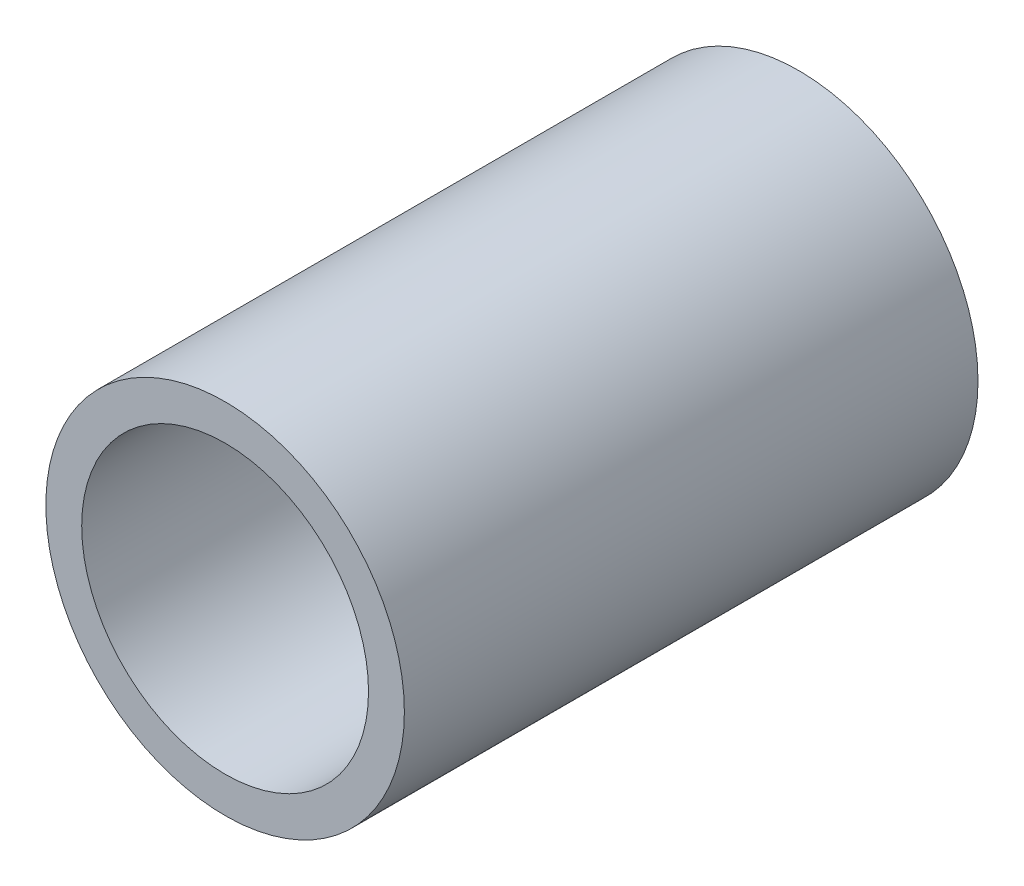
SolidWorks part; units mm, degrees
ref_plane "Front Plane" through (0, 0, 0) normal (0, 0, 1) x (1, 0, 0)
ref_plane "Top Plane" through (0, 0, 0) normal (0, 1, 0) x (1, 0, 0)
ref_plane "Right Plane" through (0, 0, 0) normal (1, 0, 0) x (0, 0, -1)
sketch "Sketch1" plane through (0, 0, 0) normal (0, 0, 1) x (1, 0, 0)
  circle A0 centre (0, 0) radius 7.5
  circle A1 centre (0, 0) radius 6
  dimension "D1" = 15
  dimension "D2" = 12
extrude "Boss-Extrude1" add sketch "Sketch1" along normal blind 24
